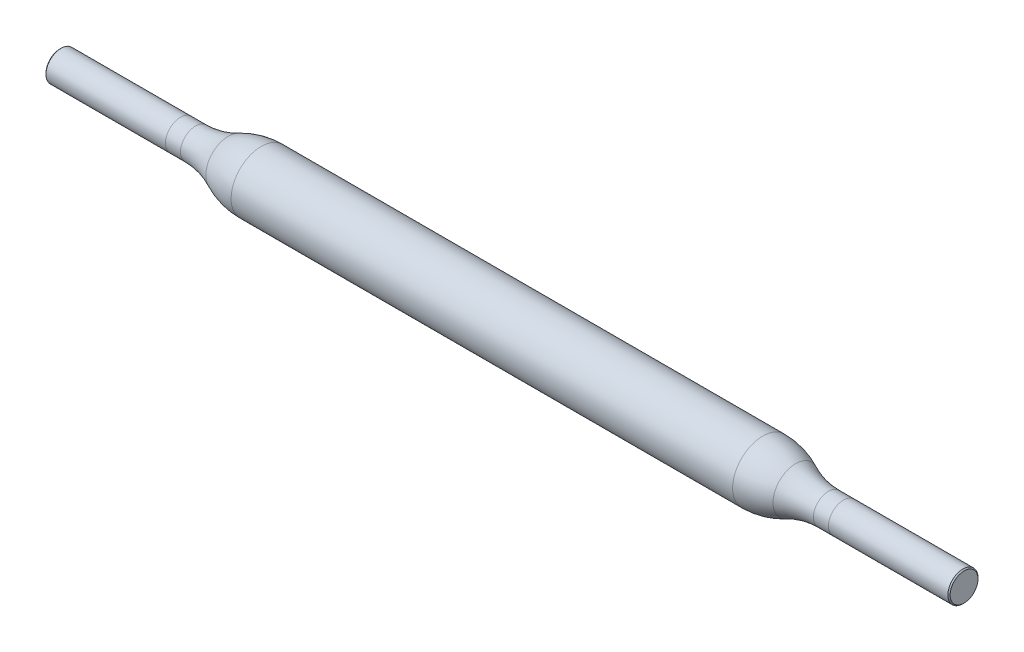
SolidWorks part; units mm, degrees
ref_plane "Front Plane" through (0, 0, 0) normal (0, 0, 1) x (1, 0, 0)
ref_plane "Top Plane" through (0, 0, 0) normal (0, 1, 0) x (1, 0, 0)
ref_plane "Right Plane" through (0, 0, 0) normal (1, 0, 0) x (0, 0, -1)
sketch "Sketch1" plane through (0, 0, 0) normal (0, 0, 1) x (1, 0, 0)
  line L0 (-30, 0) -> (30, 0)
  line L1 (30, 0) -> (30, 1)
  line L2 (-30, 0) -> (-30, 1)
  line L3 (-30, 1) -> (-21, 1)
  line L4 (-16.6411, 2) -> (16.6411, 2)
  line L5 (30, 1) -> (21, 1)
  arc A0 (-21, 1) -> (-18.8206, 1.5) centre (-21, 6) ccw
  arc A1 (21, 1) -> (18.8206, 1.5) centre (21, 6) cw
  arc A2 (16.6411, 2) -> (18.8206, 1.5) centre (16.6411, -3) cw
  arc A3 (-16.6411, 2) -> (-18.8206, 1.5) centre (-16.6411, -3) ccw
  point P2 (0, 0)
  point P8 (0, 2)
  point P17 (-18, 2)
  dimension "D7" = 5
  dimension "D1" = 60
  dimension "D2" = 1
  dimension "D3" = 9
  dimension "D4" = 9
  dimension "D5" = 2
  dimension "D6" = 3
revolve "Revolve1" add sketch "Sketch1" angle 360 about L0
sketch "Sketch2" plane through (0, 0, 0) normal (0, 0, 1) x (1, 0, 0)
  line L0 (-22, 4.429) -> (-22, -4.4937)
  line L1 (-30, 1) -> (-30, -1) construction
  line L2 (22, 4.429) -> (22, -4.4937)
  line L3 (30, -1) -> (30, 1) construction
  dimension "D1" = 8
  dimension "D2" = 8
split line "Split Line1"
chamfer "Chamfer1" distance 0.075 angle 45 2 edges at (-30, -1, 0) (30, -1, 0)
